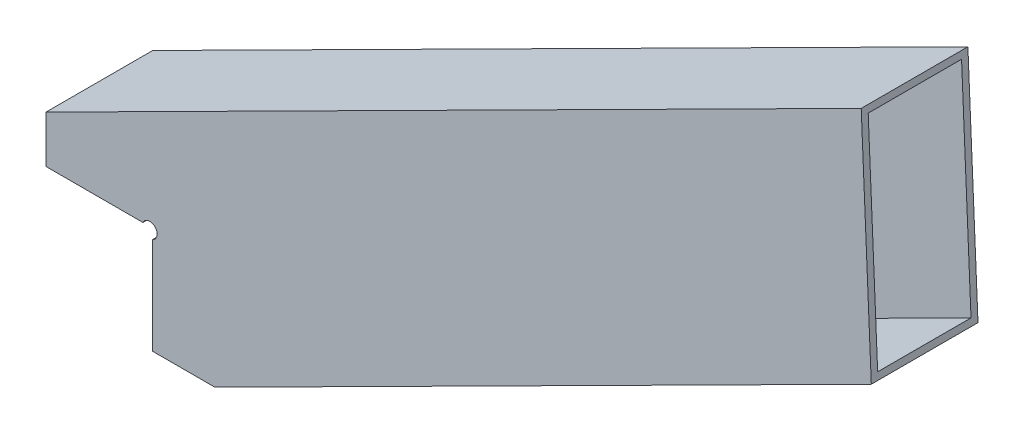
SolidWorks part; units mm, degrees
material "PET"
ref_plane "Front" through (0, 0, 0) normal (0, 0, 1) x (1, 0, 0)
ref_plane "Top" through (0, 0, 0) normal (0, 1, 0) x (1, 0, 0)
ref_plane "Right" through (0, 0, 0) normal (1, 0, 0) x (0, 0, -1)
sketch "Sketch1" plane through (0, 0, 0) normal (0, 0, 1) x (1, 0, 0)
  line L0 (181.9056, -95.6872) -> (171.8384, 137.5979) construction
  line L1 (0, 0) -> (-50.8, 0) construction
  line L2 (0, 0) -> (0, 25.4) construction
  line L3 (0, 25.4) -> (-50.8, 25.4) construction
  line L4 (-50.8, 0) -> (-50.8, 25.4) construction
  line L5 (181.9056, -95.6872) -> (207.3056, -95.6872) construction
  line L6 (171.8384, 137.5979) -> (-22.225, 39.8003)
  line L7 (174.241, 81.9226) -> (17.9792, 3.175)
  line L9 (171.8384, 137.5979) -> (174.241, 81.9226)
  line L11 (3.175, 3.175) -> (3.175, 28.575)
  line L12 (3.175, 28.575) -> (-22.225, 28.575) construction
  line L15 (-22.225, 28.575) -> (3.175, 28.575)
  line L16 (-50.8, 25.4) -> (-44.4997, 28.575) construction
  line L17 (-22.225, 39.8003) -> (-22.225, 28.575)
  line L18 (3.175, 3.175) -> (17.9792, 3.175)
  dimension "D1" = 50.8
  dimension "D2" = 25.4
  dimension "D3" = 92.471
  dimension "D4" = 112.1979
  dimension "D6" = 25.4
  dimension "D7" = 233.5022
  dimension "D8" = 50.8
  dimension "D9" = 65.725
  dimension "D10" = 249.3115
  dimension "D11" = 3.175
  dimension "D12" = 3.175
  dimension "D13" = 25.4
  dimension "D14" = 25.4
  dimension "D15" = 181.9056
extrude "Boss-Extrude1" add sketch "Sketch1" along normal blind 25.4
shell "Shell1" thickness 1.5875
sketch "Sketch2" plane through (0, 0, 25.4) normal (0, 0, 1) x (1, 0, 0)
  line L0 (2.4613, 27.8613) -> (3.175, 28.575) construction
  line L2 (-22.225, 28.575) -> (3.175, 28.575) construction
  line L4 (3.175, 28.575) -> (3.175, 3.175) construction
  line L5 (0.8401, 28.575) -> (3.175, 26.2401) construction
  circle A0 centre (2.4613, 27.8613) radius 1.7713
  dimension "D2" = 0.762
  dimension "D3" = 3.302
extrude "Cut-Extrude1" cut sketch "Sketch2" against normal through all
